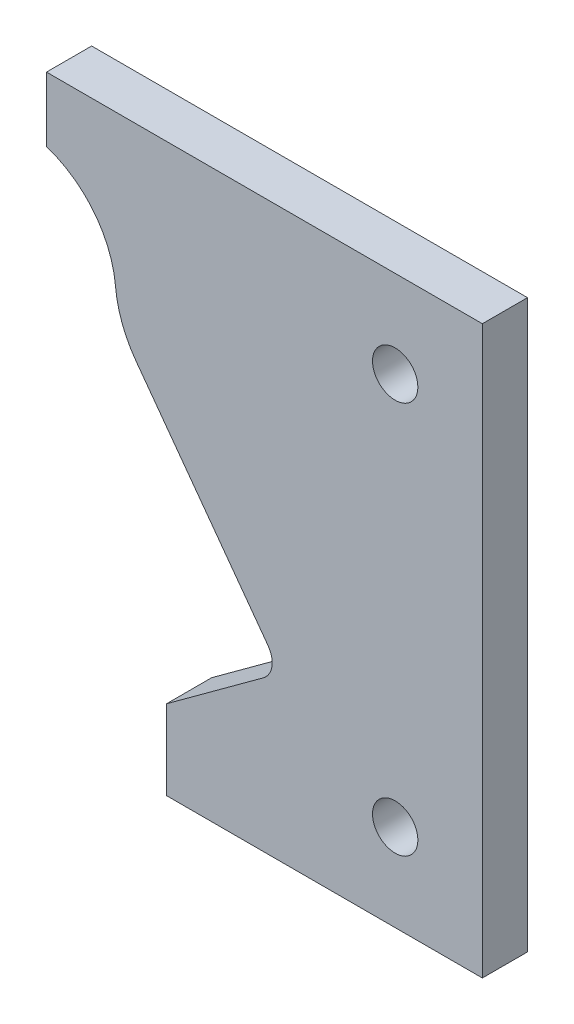
SolidWorks part; units mm, degrees
material "6061 Alloy"
ref_plane "X-Y Datum" through (0, 0, 0) normal (0, 0, 1) x (1, 0, 0)
ref_plane "X-Z Datum" through (0, 0, 0) normal (0, 1, 0) x (1, 0, 0)
ref_plane "Y-Z Datum" through (0, 0, 0) normal (1, 0, 0) x (0, 0, -1)
sketch "Sketch1" plane through (0, 0, 0) normal (0, 0, 1) x (1, 0, 0)
  line L8 (9.4387, -30.8019) -> (26.0927, -18.6139)
  line L9 (26.0927, -18.6139) -> (5.0088, 10.1959)
  line L24 (-8.0497, 30.754) -> (-8.0497, 40.152)
  line L25 (-8.0497, 40.152) -> (55.4503, 40.152)
  line L26 (55.4503, 40.152) -> (55.4503, -42.398)
  line L27 (55.4503, -42.398) -> (9.4387, -42.398)
  line L28 (9.4387, -42.398) -> (9.4387, -30.8019)
  arc A5 (2.0101, 18.1311) -> (-25.1958, 9.2394) centre (-12.6106, 16.7992) ccw
  arc A6 (5.0088, 10.1959) -> (2.0101, 18.1311) centre (17.8196, 19.5713) cw
  dimension "D3" = 20.6375
  dimension "D7" = 82.55
  dimension "D1" = 63.5
  dimension "D5" = 15.875
  dimension "D2" = 9.398
extrude "Boss-Extrude1" add sketch "Sketch1" along normal mid plane 6.5786 contours A6 L9 L8 L28 L27 L26 L25 L24 A5
fillet "Fillet1" radius 3.175 1 edges at (26.0927, -18.6139, 0)
sketch "Sketch2" plane through (0, 0, 3.2893) normal (0, 0, 1) x (1, 0, 0)
  line L0 (55.4503, 40.152) -> (55.4503, -42.398) construction
  line L1 (-8.0497, 40.152) -> (55.4503, 40.152) construction
  line L2 (55.4503, -42.398) -> (9.4387, -42.398) construction
  point P0 (42.7503, 27.452)
  point P1 (42.7503, -29.698)
  dimension "D1" = 12.7
  dimension "D2" = 12.7
  dimension "D3" = 12.7
  dimension "D4" = 12.7
hole_wizard "#97 (0.26) Diameter Hole1" positions "3DSketch1" profile "Sketch3" hole size "#97" standard "ANSI Inch" end condition through all
sketch3d "3DSketch1"
  point P0 (42.7503, 27.452, 3.2893)
  point P3 (42.7503, -29.698, 3.2893)
sketch "Sketch3" plane through (42.7503, 27.452, 3.2893) normal (1, 0, 0) x (0, -1, 0)
  line L0 (0, 0) -> (0, 6.5786)
  line L1 (0, 6.5786) -> (3.302, 6.5786)
  line L2 (3.302, 6.5786) -> (3.302, 0)
  line L5 (3.302, 0) -> (0, 0)
  line L11 (0, -6.35) -> (0, 107.95) construction
  dimension "Thru Hole Dia." = 6.604
  dimension "Thru Hole Depth" = 6.5786
